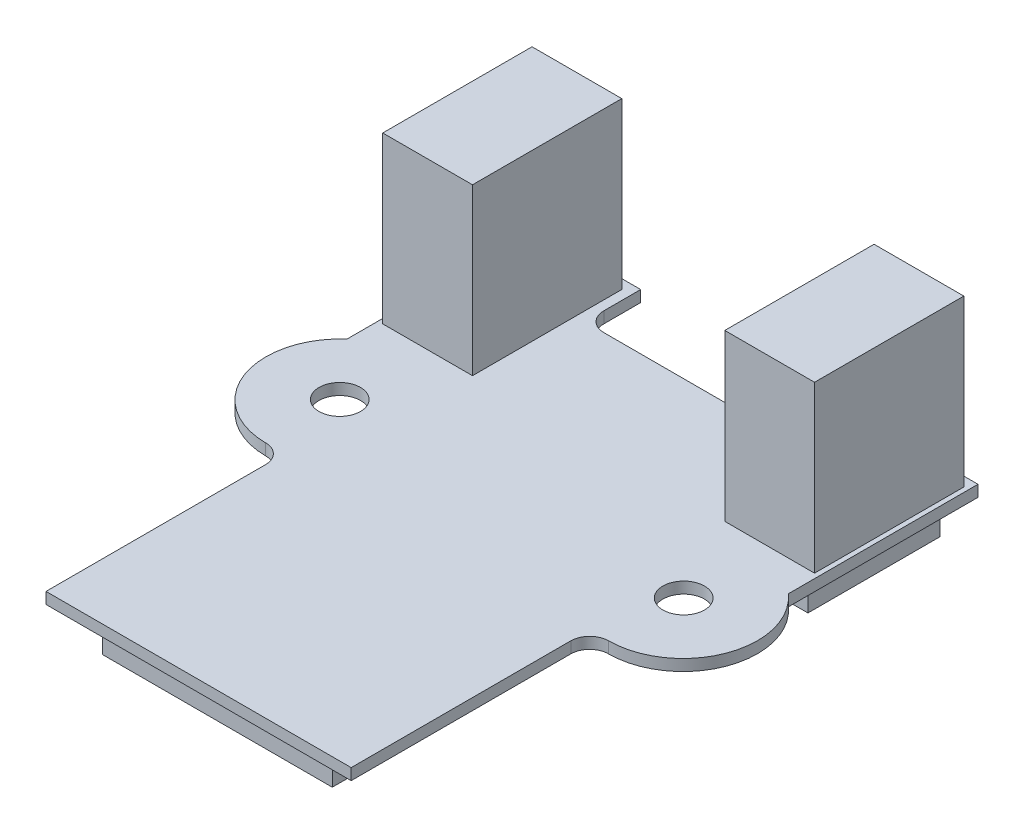
SolidWorks part; units mm, degrees
ref_plane "Front Plane" through (0, 0, 0) normal (0, 0, 1) x (1, 0, 0)
ref_plane "Top Plane" through (0, 0, 0) normal (0, 1, 0) x (1, 0, 0)
ref_plane "Right Plane" through (0, 0, 0) normal (1, 0, 0) x (0, 0, -1)
sketch "Sketch1" plane through (0, 0, 0) normal (0, 1, 0) x (1, 0, 0)
  line L0 (-40.2286, 0) -> (41.4372, 0) construction
  line L1 (0, 33.5308) -> (0, -34.192) construction
  line L2 (6.175, 10.05) -> (-6.175, 10.05)
  line L3 (-6.175, 10.05) -> (-6.175, 13)
  line L4 (-6.175, 13) -> (-11.675, 13)
  line L5 (-11.675, 13) -> (-11.675, 2.9605)
  line L6 (8.075, -3.8252) -> (8.075, -16.57)
  line L7 (-8.075, -3.8252) -> (-8.075, -16.57)
  line L8 (-8.075, -16.57) -> (8.075, -16.57)
  line L9 (11.675, 13) -> (11.675, 2.9605)
  line L10 (6.175, 13) -> (11.675, 13)
  line L11 (6.175, 10.05) -> (6.175, 13)
  arc A0 (-11.675, 2.9605) -> (-8.075, -3.8252) centre (-9.06, 0) ccw
  arc A1 (11.675, 2.9605) -> (8.075, -3.8252) centre (9.06, 0) cw
  point P9 (0, -16.57)
  point P20 (0, 10.05)
  dimension "D5" = 8.075
  dimension "D7" = 7.9
  dimension "D1" = 6.175
  dimension "D2" = 11.675
  dimension "D3" = 29.57
  dimension "D4" = 13
  dimension "D6" = 2.95
  dimension "D8" = 9.06
extrude "Boss-Extrude1" add sketch "Sketch1" along normal blind 0.6
sketch "Sketch2" plane through (0, 0.6, 0) normal (0, 1, 0) x (1, 0, 0)
  line L0 (-6.175, 13) -> (-11.675, 13) construction
  line L1 (0, 10.05) -> (0, -7.6095) construction
  line L2 (6.175, 10.05) -> (-6.175, 10.05) construction
  circle A0 centre (-9.1, 0) radius 1.1
  circle A1 centre (9.1, 0) radius 1.1
  dimension "D1" = 2.2
  dimension "D2" = 13
  dimension "D3" = 9.1
extrude "Cut-Extrude1" cut sketch "Sketch2" against normal through all
sketch "Sketch3" plane through (0, 0, 0) normal (0, -1, 0) x (1, 0, 0)
  line L0 (0, -11.5225) -> (0, 17.6003) construction
  line L1 (-6.075, 15.57) -> (6.075, 15.57)
  line L2 (-6.075, 15.57) -> (-6.075, 5)
  line L3 (-6.075, 5) -> (6.075, 5)
  line L4 (6.075, 15.57) -> (6.075, 5)
  line L5 (-6.075, 15.57) -> (6.075, 5) construction
  line L6 (-6.075, 5) -> (6.075, 15.57) construction
  line L7 (-8.075, 16.57) -> (8.075, 16.57) construction
  line L8 (-8.075, 3.8252) -> (-8.075, 16.57) construction
  line L9 (-6.175, -13) -> (-11.675, -13) construction
  line L10 (-10.675, -5) -> (-8.675, -5)
  line L11 (-10.675, -5) -> (-10.675, -12)
  line L12 (-10.675, -12) -> (-8.675, -12)
  line L13 (-8.675, -5) -> (-8.675, -12)
  line L14 (-11.675, -13) -> (-11.675, -2.9605) construction
  line L15 (10.675, -12) -> (8.675, -12)
  line L16 (10.675, -5) -> (8.675, -5)
  line L17 (8.675, -5) -> (8.675, -12)
  line L18 (10.675, -5) -> (10.675, -12)
  point P0 (0, 10.285)
  dimension "D1" = 5
  dimension "D2" = 1
  dimension "D3" = 2
  dimension "D4" = 5
  dimension "D5" = 1
  dimension "D6" = 1
  dimension "D7" = 2
extrude "Boss-Extrude2" add sketch "Sketch3" along normal blind 1.8
sketch "Sketch4" plane through (0, 0.6, 0) normal (0, 1, 0) x (1, 0, 0)
  line L0 (-11.675, 13) -> (-11.675, 2.9605) construction
  line L1 (-11.425, 12.5) -> (-6.675, 12.5)
  line L2 (-11.425, 12.5) -> (-11.425, 4.6)
  line L3 (-11.425, 4.6) -> (-6.675, 4.6)
  line L4 (-6.675, 12.5) -> (-6.675, 4.6)
  line L5 (-6.175, 13) -> (-11.675, 13) construction
  line L6 (0, 13.5853) -> (0, -17.8834) construction
  line L7 (6.675, 12.5) -> (6.675, 4.6)
  line L8 (11.425, 4.6) -> (6.675, 4.6)
  line L9 (11.425, 12.5) -> (11.425, 4.6)
  line L10 (11.425, 12.5) -> (6.675, 12.5)
  dimension "D1" = 7.9
  dimension "D2" = 4.75
  dimension "D3" = 0.25
  dimension "D4" = 0.5
extrude "Boss-Extrude3" add sketch "Sketch4" along normal blind 8.75
fillet "Fillet1" radius 1 4 edges at (-8.075, 0.3, 3.8252) (8.075, 0.3, 3.8252) (6.175, 0.3, -10.05) (-6.175, 0.3, -10.05)
